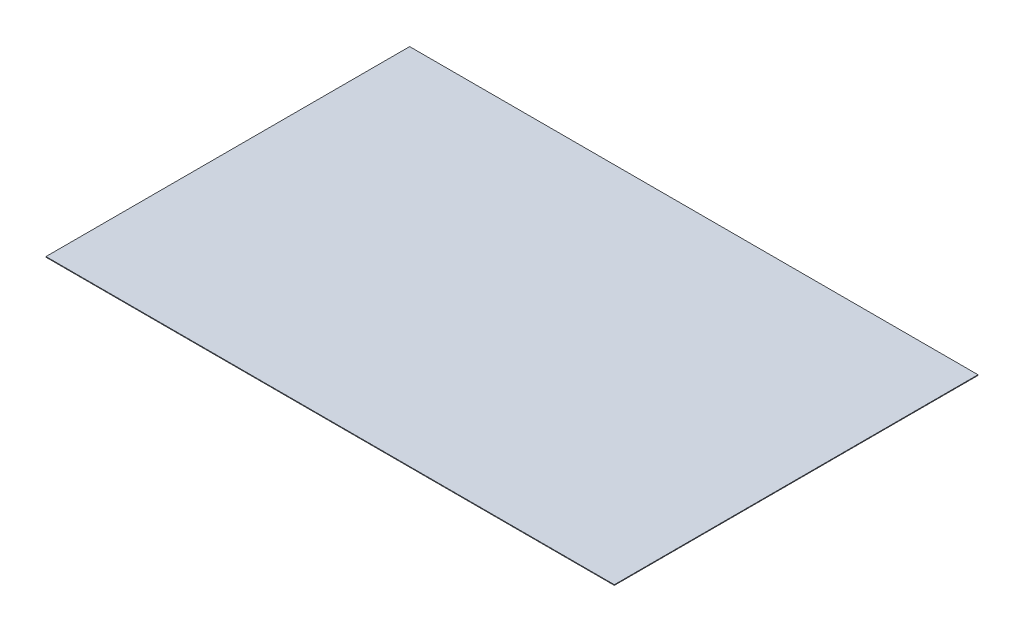
SolidWorks part; units mm, degrees
material "AISI 1020 Steel, Cold Rolled"
ref_plane "Front Plane" through (0, 0, 0) normal (0, 0, 1) x (1, 0, 0)
ref_plane "Top Plane" through (0, 0, 0) normal (0, 1, 0) x (1, 0, 0)
ref_plane "Right Plane" through (0, 0, 0) normal (1, 0, 0) x (0, 0, -1)
sketch "Sketch1" plane through (0, 0, 0) normal (0, 1, 0) x (1, 0, 0)
  line L1 (0, 0) -> (-8440, 0)
  line L2 (0, 0) -> (0, 5400)
  line L3 (0, 5400) -> (-8440, 5400)
  line L4 (-8440, 0) -> (-8440, 5400)
  dimension "D1" = 8440
  dimension "D2" = 5400
extrude "Boss-Extrude1" add sketch "Sketch1" along normal blind 9.525
